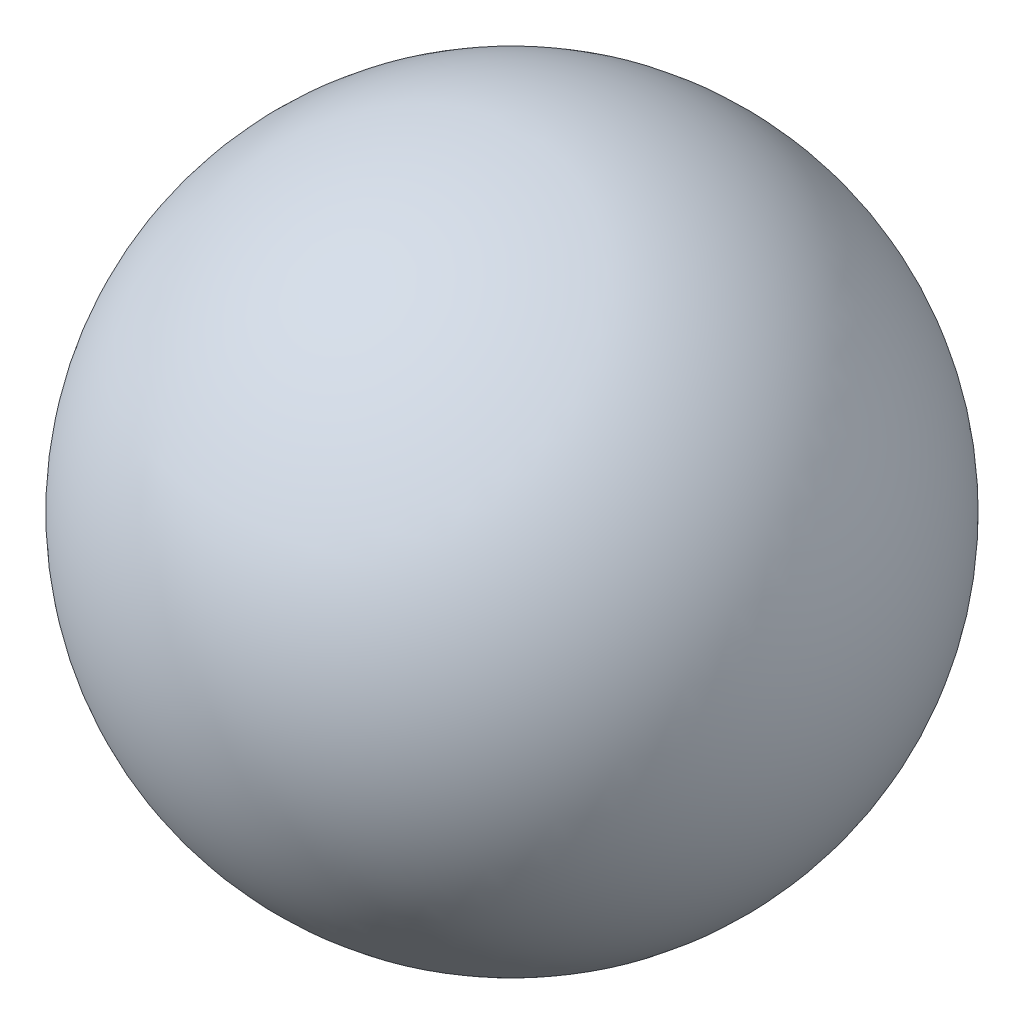
SolidWorks part; units mm, degrees
material "POLYURETHANE (11671)"
ref_plane "Front Plane" through (0, 0, 0) normal (0, 0, 1) x (1, 0, 0)
ref_plane "Top Plane" through (0, 0, 0) normal (0, 1, 0) x (1, 0, 0)
ref_plane "Right Plane" through (0, 0, 0) normal (1, 0, 0) x (0, 0, -1)
sketch "Sketch1" plane through (0, 0, 0) normal (0, 0, 1) x (1, 0, 0)
  line L0 (0, -88.9) -> (0, 88.9)
  arc A0 (0, -88.9) -> (0, 88.9) centre (0, 0) ccw
  point P6 (0, 0)
  dimension "D1" = 177.8
revolve "Revolve1" add sketch "Sketch1" angle 360 about L0
